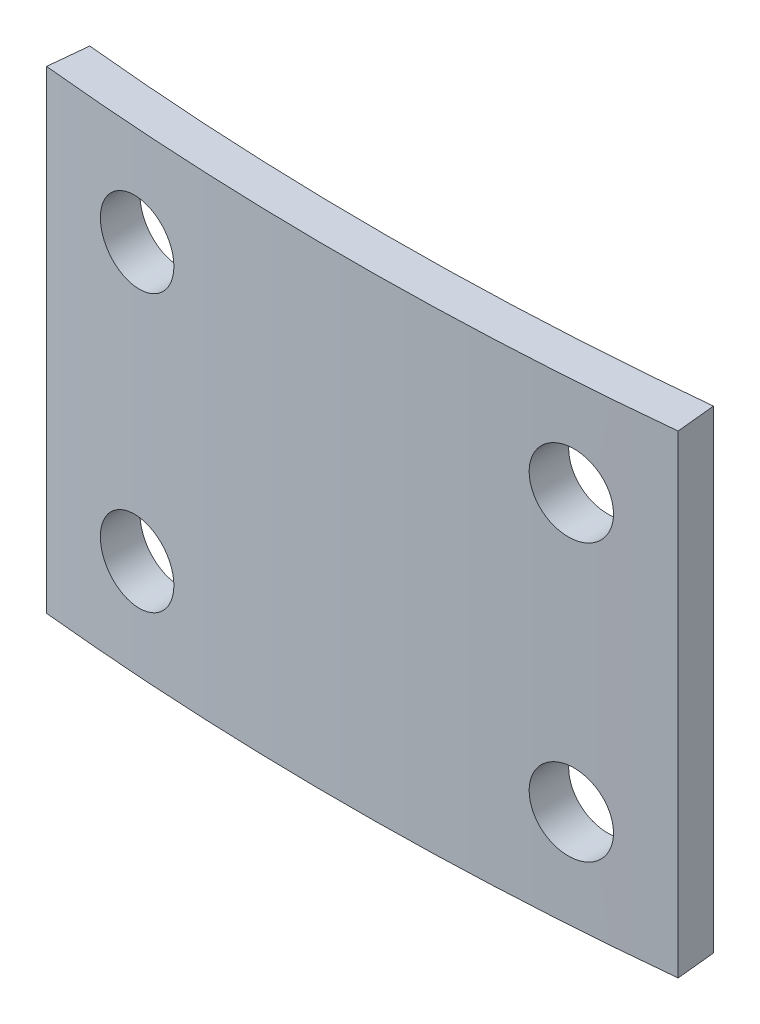
SolidWorks part; units mm, degrees
material "1023 Carbon Steel Sheet (SS)"
ref_plane "Front Plane" through (0, 0, 0) normal (0, 0, 1) x (1, 0, 0)
ref_plane "Top Plane" through (0, 0, 0) normal (0, 1, 0) x (1, 0, 0)
ref_plane "Right Plane" through (0, 0, 0) normal (1, 0, 0) x (0, 0, -1)
sketch "Sketch1" plane through (0, 0, 0) normal (0, 1, 0) x (1, 0, 0)
  line L0 (103.9807, -784.5283) -> (102.9807, -774.5785)
  line L1 (-56.0193, -784.5283) -> (-55.0193, -774.5785)
  arc A0 (-56.0193, -784.5283) -> (103.9807, -784.5283) centre (23.9807, 11.4616) ccw
  arc A1 (-55.0193, -774.5785) -> (102.9807, -774.5785) centre (23.9807, 11.4616) ccw
extrude "Boss-Extrude1" add sketch "Sketch1" along normal blind 120
sketch "Sketch2" plane through (0, 0, 0) normal (0, 0, 1) x (1, 0, 0)
  circle A0 centre (-31.0193, 95) radius 10
  circle A1 centre (78.9807, 95) radius 10
  circle A2 centre (78.9807, 25) radius 10
  circle A3 centre (-31.0193, 25) radius 10
  dimension "D3" = 20
  dimension "D4" = 20
  dimension "D5" = 20
  dimension "D6" = 20
  dimension "D2" = 110
extrude "Cut-Extrude1" cut sketch "Sketch2" against normal through all both and the other way through all
